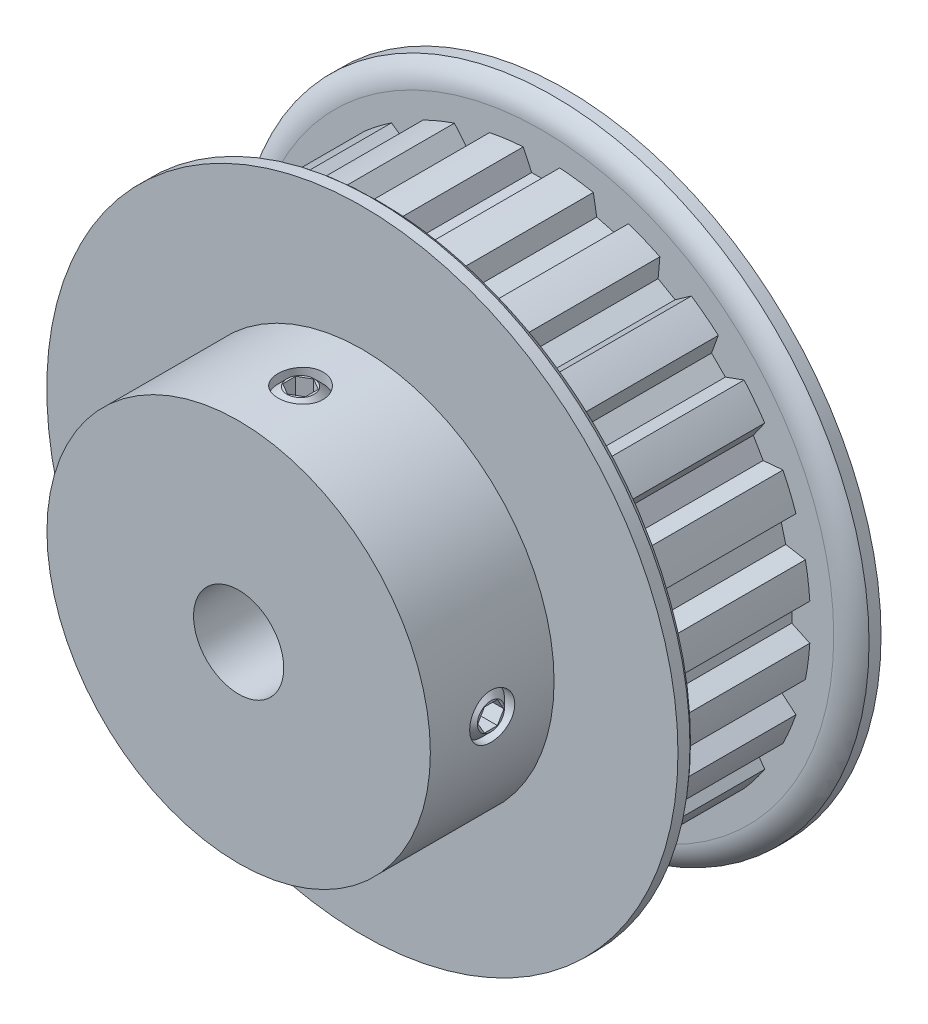
SolidWorks part; units mm, degrees
ref_plane "Front Plane" through (0, 0, 0) normal (0, 0, 1) x (1, 0, 0)
ref_plane "Top Plane" through (0, 0, 0) normal (0, 1, 0) x (1, 0, 0)
ref_plane "Right Plane" through (0, 0, 0) normal (1, 0, 0) x (0, 0, -1)
sketch "Sketch1" plane through (0, 0, 0) normal (0, 0, 1) x (1, 0, 0)
  line L0 (-1.2827, 18.8976) -> (-0.6905, 17.6276)
  line L1 (-0.6905, 17.6276) -> (0.6905, 17.6276)
  line L2 (0.6905, 17.6276) -> (1.2827, 18.8976)
  line L3 (-1.2827, 18.8976) -> (1.2827, 18.8976)
  line L4 (0, 0) -> (0, 17.6276) construction
  line L5 (0, 17.6276) -> (0, 19.9136) construction
  circle A0 centre (0, 0) radius 19.4056 construction
  circle A1 centre (0, 0) radius 22.225 construction
  circle A2 centre (0, 0) radius 18.9411 construction
  point P6 (0, 18.8976)
  point P11 (0, 19.4056)
  point P13 (0, 22.225)
  point P14 (0, 18.9411)
  dimension "D1" = 1.016
  dimension "D2" = 0.508
sketch "Sketch2" plane through (0, 0, 0) normal (1, 0, 0) x (0, 0, -1)
  line L0 (-11.5062, 3.175) -> (11.5062, 3.175)
  line L1 (-11.5062, 3.175) -> (-11.5062, 13.5001)
  line L2 (-11.5062, 13.5001) -> (-2.794, 13.5001)
  line L3 (-2.794, 13.5001) -> (-2.794, 22.225)
  line L4 (-2.794, 22.225) -> (-1.1049, 22.225) construction
  line L5 (-1.1049, 22.225) -> (-1.1049, 18.9411) construction
  line L6 (-1.1049, 18.9411) -> (9.8171, 18.9411)
  line L7 (9.8171, 18.9411) -> (9.8171, 22.225) construction
  line L8 (9.8171, 22.225) -> (11.5062, 22.225) construction
  line L9 (11.5062, 22.225) -> (11.5062, 3.175)
  line L10 (-11.5062, 0) -> (11.5062, 0) construction
  line L13 (-2.794, 22.225) -> (-1.9495, 22.225)
  line L14 (-1.1049, 20.583) -> (-1.1049, 18.9411)
  line L15 (9.8171, 18.9411) -> (9.8171, 20.583)
  line L16 (10.6616, 22.225) -> (11.5062, 22.225)
  arc A0 (-1.1049, 20.583) -> (-1.9495, 22.225) centre (-3.1233, 20.583) ccw
  arc A1 (9.8171, 20.583) -> (10.6616, 22.225) centre (11.8355, 20.583) cw
  point P12 (-1.1049, 20.583)
  point P14 (-1.9495, 22.225)
  point P20 (9.8171, 20.583)
  point P21 (10.6616, 22.225)
  point P25 (9.8171, 0)
  point P26 (-1.1049, 0)
  dimension "Bore" = 6.35
  dimension "Hub Dia" = 27.0002
  dimension "Outside Width" = 14.3002
  dimension "Inside Width" = 10.922
revolve "Revolve1" add sketch "Sketch2" angle 360 mid plane about L10
sketch "Sketch3" plane through (0, 0, 0) normal (0, 0, 1) x (1, 0, 0)
  line L0 (-0.6905, 17.6276) -> (0.6905, 17.6276) construction
  line L1 (0.6905, 17.6276) -> (1.2827, 18.8976) construction
  line L2 (-1.2827, 18.8976) -> (-0.6905, 17.6276) construction
  line L3 (-0.6905, 17.6276) -> (0.6905, 17.6276)
  line L4 (0.6905, 17.6276) -> (1.2827, 18.8976)
  line L5 (-1.2827, 18.8976) -> (-0.6905, 17.6276)
  circle A0 centre (0, 0) radius 18.9411 construction
  arc A1 (1.2827, 18.8976) -> (-1.2827, 18.8976) centre (0, 0) ccw
extrude "Cut-Extrude1" cut sketch "Sketch3" against normal up to vertex (9.8171 mm away) from vertex at 1.1049 starting at point (0, 18.9411, 1.1049)
pattern_circular "CirPattern1" count 24 over 360 about axis through (0, 0, 0) along (0, 0, 1) of "Cut-Extrude1"
sketch "Sketch4" plane through (0, 0, 0) normal (0, 1, 0) x (1, 0, 0)
  line L0 (0, -2.794) -> (0, -11.5062) construction
  line L1 (-13.5001, -2.794) -> (13.5001, -2.794) construction
  line L2 (-13.5001, -11.5062) -> (13.5001, -11.5062) construction
  circle A0 centre (0, -7.1501) radius 1.5875
  dimension "D1" = 3.175
extrude "Cut-Extrude2" cut sketch "Sketch4" along normal through all
ref_plane "Plane1" through (0, 0, 7.1501) normal (0, 0, 1) x (1, 0, 0)
sketch "Sketch5" plane through (0, 0, 7.1501) normal (0, 0, 1) x (1, 0, 0)
  line L0 (0, 0) -> (0, 13.5001) construction
  line L1 (-1.5875, 13.4064) -> (-1.5875, 2.7496) construction
  line L2 (-1.5875, 13.4064) -> (-1.5875, 2.7496) construction
  line L3 (0, 13.4064) -> (0, 3.175)
  line L4 (0, 3.175) -> (-0.9525, 3.175)
  line L5 (-1.5875, 12.7714) -> (-1.5875, 3.81)
  line L6 (-0.9525, 13.4064) -> (0, 13.4064)
  line L7 (-1.5875, 12.7714) -> (-0.9525, 13.4064)
  line L8 (-1.5875, 3.81) -> (-0.9525, 3.175)
  circle A0 centre (0, 0) radius 13.5001 construction
  circle A3 centre (0, 0) radius 3.175 construction
  point P13 (-1.5875, 3.175)
  point P15 (-1.5875, 13.4064)
revolve "Revolve2" add sketch "Sketch5" angle 360 mid plane about L0
sketch "Sketch6" plane through (0, 13.4064, 0) normal (0, -1, 0) x (-1, 0, 0)
  line L1 (0, -6.2336) -> (-0.7938, -6.6918)
  line L2 (-0.7938, -6.6918) -> (-0.7937, -7.6084)
  line L3 (-0.7937, -7.6084) -> (0, -8.0666)
  line L4 (0, -8.0666) -> (0.7938, -7.6084)
  line L5 (0.7938, -7.6084) -> (0.7938, -6.6918)
  line L6 (0.7938, -6.6918) -> (0, -6.2336)
  circle A0 centre (0, -7.1501) radius 0.7938 construction
  dimension "D1" = 1.5875
extrude "Cut-Extrude3" cut sketch "Sketch6" along normal blind 1.1906
pattern_circular "CirPattern2" count 2 every 90 about axis through (0, 0, 0) along (0, 0, 1) of "Cut-Extrude2", "Revolve2", "Cut-Extrude3"
equation "\"D2@Sketch1\" = \"D1@Sketch1\"/2"
equation "\"D1@Sketch4\" = \"Bore@Sketch2\"/2"
equation "\"D1@Sketch6\" = \"D1@Sketch4\"/2"
equation "\"D1@Cut-Extrude3\" = \"D1@Sketch6\"*.75"
